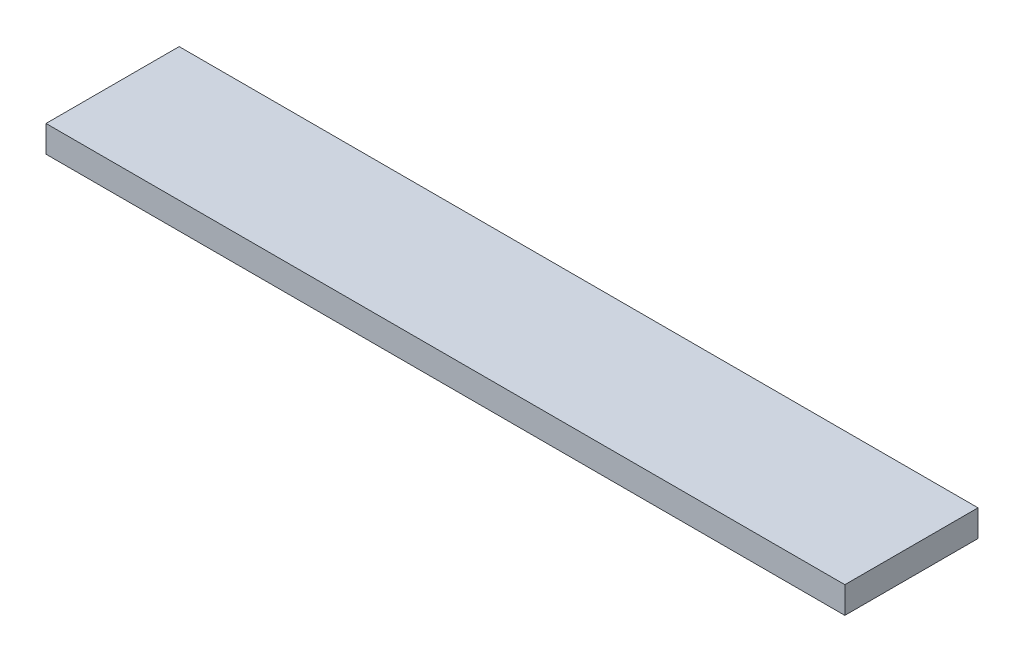
SolidWorks part; units mm, degrees
ref_plane "Front Plane" through (0, 0, 0) normal (0, 0, 1) x (1, 0, 0)
ref_plane "Top Plane" through (0, 0, 0) normal (0, 1, 0) x (1, 0, 0)
ref_plane "Right Plane" through (0, 0, 0) normal (1, 0, 0) x (0, 0, -1)
sketch "Sketch1" plane through (0, 0, 0) normal (0, 1, 0) x (1, 0, 0)
  line L1 (-150, 25) -> (150, 25)
  line L2 (-150, 25) -> (-150, -25)
  line L3 (-150, -25) -> (150, -25)
  line L4 (150, 25) -> (150, -25)
  point P4 (0, -25)
  point P6 (0, 25)
  point P7 (-150, 0)
  dimension "D1" = 50
  dimension "D2" = 300
extrude "Boss-Extrude1" add sketch "Sketch1" along normal blind 10
